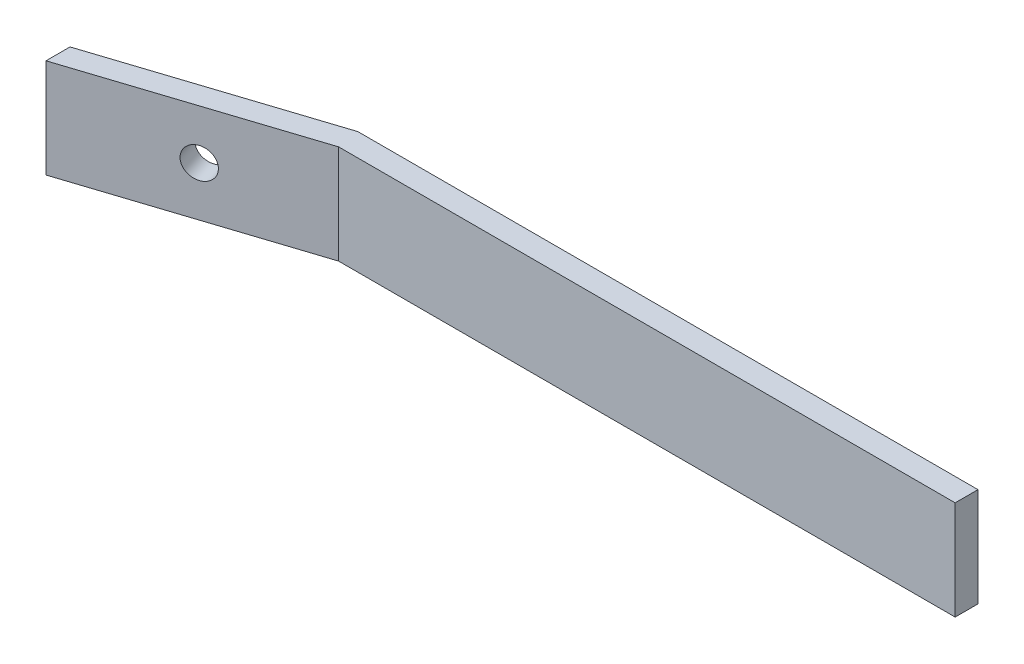
SolidWorks part; units mm, degrees
ref_plane "Front Plane" through (0, 0, 0) normal (0, 0, 1) x (1, 0, 0)
ref_plane "Top Plane" through (0, 0, 0) normal (0, 1, 0) x (1, 0, 0)
ref_plane "Right Plane" through (0, 0, 0) normal (1, 0, 0) x (0, 0, -1)
sketch "Sketch1" plane through (0, 0, 0) normal (0, 0, 1) x (1, 0, 0)
  line L1 (-75, 6.5) -> (75, 6.5)
  line L2 (-75, 6.5) -> (-75, -6.5)
  line L3 (-75, -6.5) -> (75, -6.5)
  line L4 (75, 6.5) -> (75, -6.5)
  line L5 (-75, 6.5) -> (75, -6.5) construction
  line L6 (-75, -6.5) -> (75, 6.5) construction
  point P0 (0, 0)
  dimension "D1" = 13
  dimension "D2" = 150
extrude "Boss-Extrude1" add sketch "Sketch1" along normal blind 40
sketch "Sketch2" plane through (0, -6.5, 0) normal (0, -1, 0) x (1, 0, 0)
  line L0 (-75, 9.2705) -> (-46.4683, 0)
  line L1 (-75, 40) -> (-75, 0) construction
  line L2 (-75, 0) -> (75, 0) construction
  line L3 (-75, 9.2705) -> (-75, 0)
  line L4 (-75, 0) -> (-46.4683, 0)
  dimension "D1" = 30
  dimension "D2" = 162
extrude "Cut-Extrude1" cut sketch "Sketch2" against normal blind 40
sketch "Sketch3" plane through (0, -6.5, 0) normal (0, -1, 0) x (1, 0, 0)
  line L0 (-75, 12.4249) -> (-45.9932, 3)
  line L1 (-75, 40) -> (-75, 9.2705) construction
  line L2 (75, 40) -> (75, 0) construction
  line L3 (75, 3) -> (-45.9932, 3)
  line L4 (-46.4683, 0) -> (-75, 9.2705) construction
  line L5 (-46.4683, 0) -> (75, 0) construction
  line L6 (-75, 12.4249) -> (-75, 40)
  line L7 (-75, 40) -> (75, 40)
  line L8 (75, 40) -> (75, 3)
  dimension "D1" = 3
  dimension "D2" = 3
extrude "Cut-Extrude3" cut sketch "Sketch3" against normal through all
sketch "Sketch4" plane through (0, 0, 0) normal (0, 0, 1) x (1, 0, 0)
  line L0 (75, 6.5) -> (75, -6.5) construction
  line L1 (75, 6.5) -> (35, 6.5)
  line L2 (75, 6.5) -> (75, -6.5)
  line L3 (75, -6.5) -> (35, -6.5)
  line L4 (35, 6.5) -> (35, -6.5)
  line L5 (-46.4683, -6.5) -> (75, -6.5) construction
  line L6 (75, 6.5) -> (-46.4683, 6.5) construction
  dimension "D1" = 0
  dimension "D2" = 0
  dimension "D3" = 40
sketch "Sketch8" plane through (-4.4373, 0, -13.6567) normal (-0.309, 0, -0.9511) x (-0.9511, 0, 0.309)
  line L1 (44.194, 6.5) -> (74.194, 6.5) construction
  line L2 (44.194, -6.5) -> (44.194, 6.5) construction
  circle A0 centre (59.194, 0) radius 2
  dimension "D1" = 4
  dimension "D2" = 6.5
  dimension "D3" = 15
extrude "Cut-Extrude7" cut sketch "Sketch8" against normal blind 6.5
extrude "Cut-Extrude10" cut sketch "Sketch4" along normal through all
